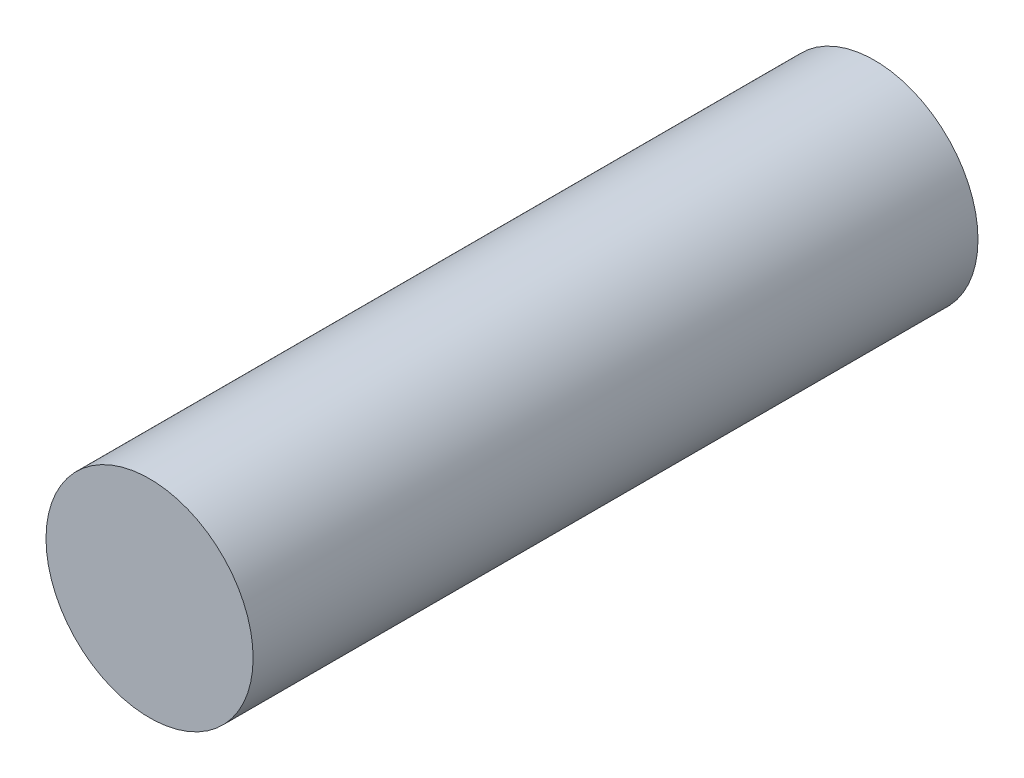
SolidWorks part; units mm, degrees
ref_plane "Front Plane" through (0, 0, 0) normal (0, 0, 1) x (1, 0, 0)
ref_plane "Top Plane" through (0, 0, 0) normal (0, 1, 0) x (1, 0, 0)
ref_plane "Right Plane" through (0, 0, 0) normal (1, 0, 0) x (0, 0, -1)
sketch "Sketch1" plane through (0, 0, 0) normal (0, 0, 1) x (1, 0, 0)
  circle A0 centre (0, 0) radius 6.35
  dimension "D1" = 12.7
extrude "Boss-Extrude1" add sketch "Sketch1" along normal blind 44.45
